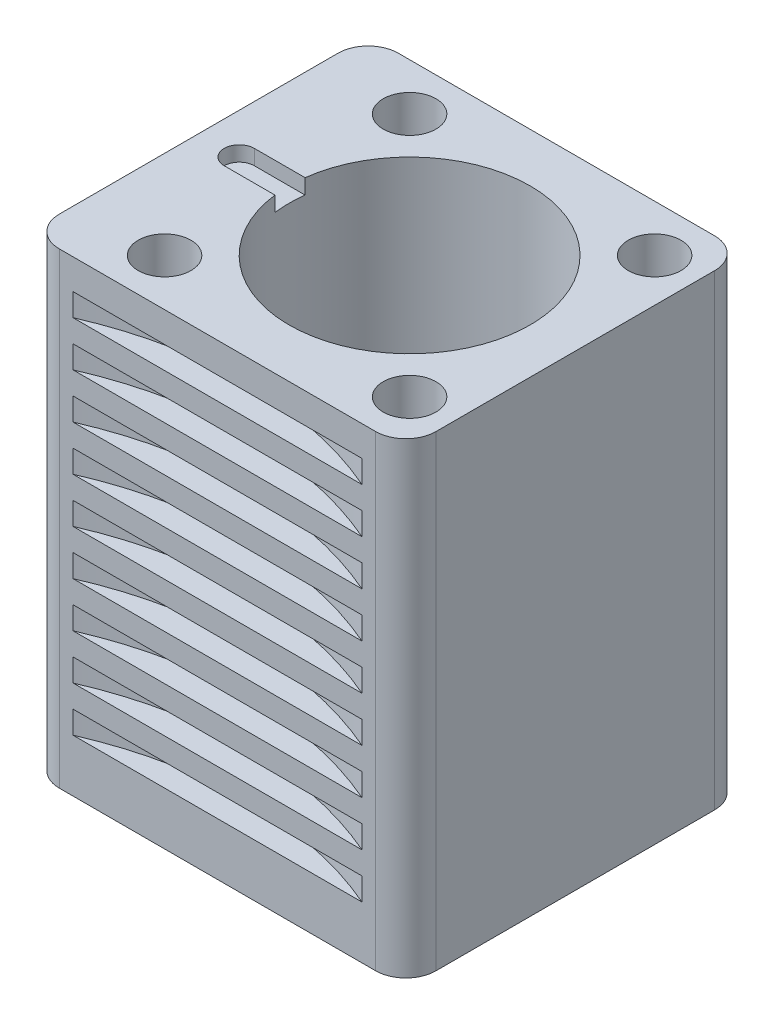
SolidWorks part; units mm, degrees
ref_plane "Front Plane" through (0, 0, 0) normal (0, 0, 1) x (1, 0, 0)
ref_plane "Top Plane" through (0, 0, 0) normal (0, 1, 0) x (1, 0, 0)
ref_plane "Right Plane" through (0, 0, 0) normal (1, 0, 0) x (0, 0, -1)
sketch "Sketch1" plane through (0, 0, 0) normal (0, 1, 0) x (1, 0, 0)
  line L1 (18, 22.5) -> (-24, 22.5)
  line L2 (22, 18.5) -> (22, -18.5)
  line L3 (18, -22.5) -> (-24, -22.5)
  line L4 (-28, 18.5) -> (-28, -18.5)
  arc A0 (-24, 22.5) -> (-28, 18.5) centre (-24, 18.5) ccw
  arc A1 (22, -18.5) -> (18, -22.5) centre (18, -18.5) cw
  arc A2 (-24, -22.5) -> (-28, -18.5) centre (-24, -18.5) cw
  arc A3 (18, 22.5) -> (22, 18.5) centre (18, 18.5) cw
  point P7 (-28, 22.5)
  point P10 (22, -22.5)
  point P15 (22, 22.5)
  dimension "D5" = 4
  dimension "D1" = 50
  dimension "D2" = 45
  dimension "D3" = 22
  dimension "D4" = 22.5
extrude "Boss-Extrude1" add sketch "Sketch1" along normal blind 62
sketch "Sketch2" plane through (0, 0, 0) normal (0, -1, 0) x (1, 0, 0)
  circle A0 centre (0, 0) radius 18
  dimension "D1" = 36
extrude "Boss-Extrude2" add sketch "Sketch2" along normal blind 2
sketch "Sketch3" plane through (0, -2, 0) normal (0, -1, 0) x (-1, 0, 0)
  circle A0 centre (0, 0) radius 16
  dimension "D1" = 32
extrude "Cut-Extrude1" cut sketch "Sketch3" against normal through all both
sketch "Sketch4" plane through (0, 62, 0) normal (0, 1, 0) x (1, 0, 0)
  line L0 (-28, 18.5) -> (-28, -18.5) construction
  line L1 (-9.0375, 2) -> (-22.61, 2)
  line L2 (-9.0375, 2) -> (-9.0375, -2)
  line L3 (-9.0375, -2) -> (-22.61, -2)
  arc A0 (-22.61, 2) -> (-22.61, -2) centre (-22.61, 0) ccw
  dimension "D3" = 5.39
  dimension "D1" = 2
  dimension "D2" = 4
extrude "Cut-Extrude2" cut sketch "Sketch4" against normal blind 2
sketch "Sketch5" plane through (0, 62, 0) normal (0, 1, 0) x (1, 0, 0)
  line L0 (0, 0) -> (23, 0) construction
  line L1 (0, 0) -> (16.2635, 16.2635) construction
  circle A0 centre (0, 0) radius 23 construction
  circle A1 centre (16.2635, 16.2635) radius 3.5
  circle A2 centre (16.2635, -16.2635) radius 3.5
  circle A3 centre (-16.2635, -16.2635) radius 3.5
  circle A4 centre (-16.2635, 16.2635) radius 3.5
  point P15 (0, 0)
  dimension "D1" = 46
  dimension "D3" = 7
  dimension "D2" = 45
  dimension "D4" = 4
extrude "Cut-Extrude3" cut sketch "Sketch5" against normal through all
ref_plane "Plane2" through (-3, 0, 0) normal (1, 0, 0) x (0, 0, -1)
sketch "Sketch6" plane through (-3, 0, 0) normal (1, 0, 0) x (0, 0, -1)
  line L0 (-18.5, 62) -> (-22.5, 62) construction
  line L1 (-66.5, 58) -> (-18.5, 58)
  line L2 (-66.5, 58) -> (-66.5, 55)
  line L3 (-66.5, 55) -> (-18.5, 55)
  line L4 (-18.5, 58) -> (-18.5, 55)
  dimension "D1" = 4
  dimension "D2" = 4
  dimension "D3" = 48
  dimension "D4" = 3
revolve "Cut-Revolve2" cut sketch "Sketch6" angle 360 about L2
pattern_linear "LPattern2" count 9 spacing 6 along (0, -1, 0) of "Cut-Revolve2"
mirror "Mirror2" about plane through (0, 0, 0) normal (0, 0, 1) of "LPattern2", "Cut-Revolve2"
sketch "Sketch11" plane through (0, 0, 0) normal (0, 0, 1) x (1, 0, 0)
  line L0 (-28, 62) -> (-28, 0) construction
  line L1 (-24, 58) -> (-72, 58)
  line L2 (-24, 58) -> (-24, 55)
  line L3 (-24, 55) -> (-72, 55)
  line L4 (-72, 58) -> (-72, 55)
  line L5 (-24, 62) -> (-28, 62) construction
  dimension "D1" = 4
  dimension "D2" = 4
  dimension "D3" = 3
  dimension "D4" = 48
revolve "Cut-Revolve4" cut sketch "Sketch11" angle 360 about L4
pattern_linear "LPattern4" count 9 spacing 6 along (0, -1, 0) of "Cut-Revolve4"
